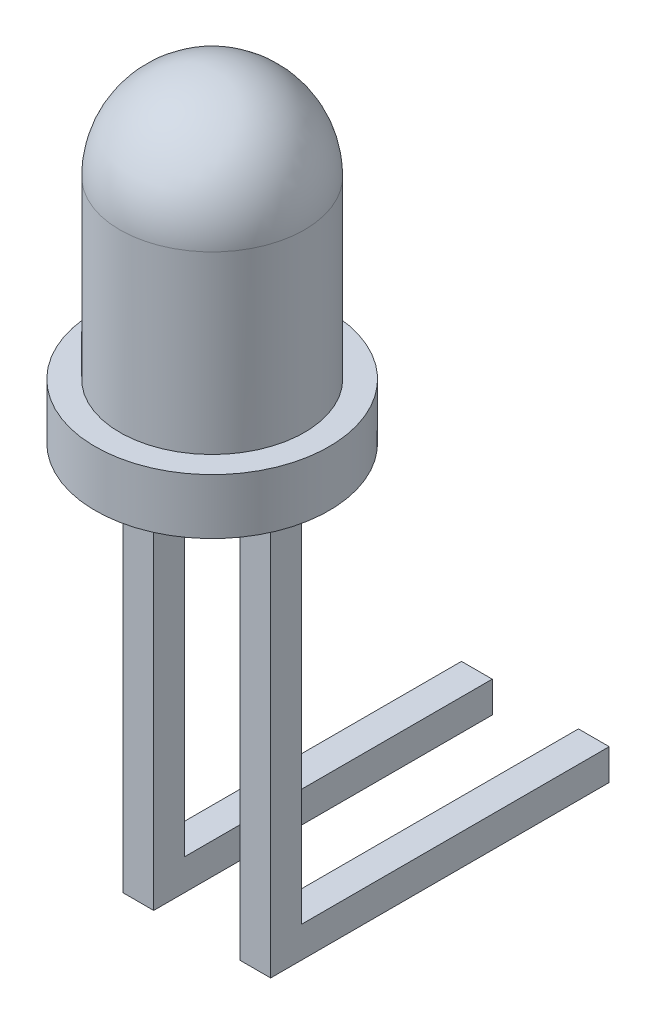
SolidWorks part; units mm, degrees
ref_plane "Přední rovina" through (0, 0, 0) normal (0, 0, 1) x (1, 0, 0)
ref_plane "Horní rovina" through (0, 0, 0) normal (0, 1, 0) x (1, 0, 0)
ref_plane "Pravá rovina" through (0, 0, 0) normal (1, 0, 0) x (0, 0, -1)
sketch "Skica1" plane through (0, 0, 0) normal (0, 0, 1) x (1, 0, 0)
  line L0 (-1.5, 6.0665) -> (-1.5, 3.2165)
  line L1 (-1.9, 2.3165) -> (0, 2.3165)
  line L2 (0, 7.5665) -> (0, 2.3165)
  line L3 (-1.5, 3.2165) -> (-1.9, 3.2165)
  line L4 (-1.9, 3.2165) -> (-1.9, 2.3165)
  line L5 (0, 7.5665) -> (0, 2.3165) construction
  arc A0 (0, 7.5665) -> (-1.5, 6.0665) centre (0, 6.0665) ccw
  dimension "D1" = 0.9
  dimension "D2" = 5.25
  dimension "D3" = 3.8
  dimension "D4" = 2.85
revolve "Rotovat1" add sketch "Skica1" angle 360 about L5
sketch "Skica2" plane through (0, 0, 0) normal (0, 0, 1) x (1, 0, 0)
  line L0 (0.7, 2.3165) -> (1.2, 2.3165)
  line L1 (-1.9, 2.3165) -> (1.9, 2.3165) construction
  line L2 (1.2, 2.3165) -> (1.2, -4.4835)
  line L3 (-0.7, -4.4835) -> (-1.2, -4.4835)
  line L4 (1.2, -4.4835) -> (0.7, -4.4835)
  line L6 (0.7, -4.4835) -> (0.7, 2.3165)
  line L7 (-0.7, 2.3165) -> (-0.7, -4.4835)
  line L11 (-1.2, -4.4835) -> (-1.2, 2.3165)
  line L12 (-0.7, 2.3165) -> (-1.2, 2.3165)
  dimension "D1" = 0.5
  dimension "D2" = 6.8
  dimension "D3" = 0.7
  dimension "D4" = 0.7
  dimension "D5" = 0.5
  dimension "D7" = 6.8
extrude "Přidat vysunutím1" add sketch "Skica2" along normal mid plane 0.5
sketch "Skica3" plane through (0, 0, -0.25) normal (0, 0, -1) x (-1, 0, 0)
  line L0 (0.7, -4.4835) -> (0.7, 2.3165) construction
  line L1 (1.2, -4.4835) -> (0.7, -4.4835)
  line L2 (1.2, -4.4835) -> (1.2, -3.9787)
  line L3 (1.2, -3.9787) -> (0.7, -3.9787)
  line L4 (0.7, -4.4835) -> (0.7, -3.9787)
  line L5 (-1.2, -4.4835) -> (-1.2, 2.3165) construction
  line L6 (-0.7, -4.4835) -> (-1.2, -4.4835)
  line L7 (-0.7, -4.4835) -> (-0.7, -3.9787)
  line L8 (-0.7, -3.9787) -> (-1.2, -3.9787)
  line L9 (-1.2, -4.4835) -> (-1.2, -3.9787)
  dimension "D1" = 0.5048
  dimension "D2" = 0.5048
extrude "Přidat vysunutím2" add sketch "Skica3" along normal blind 5
